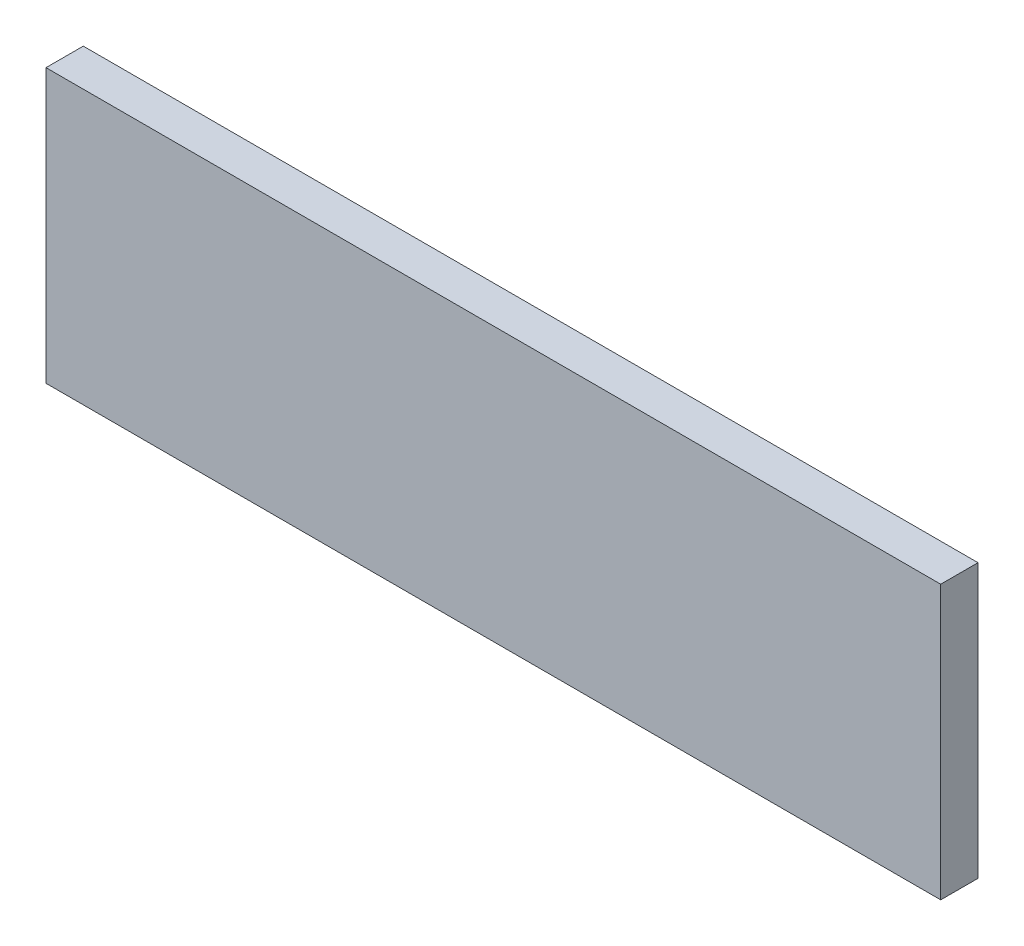
SolidWorks part; units mm, degrees
ref_plane "Front Plane" through (0, 0, 0) normal (0, 0, 1) x (1, 0, 0)
ref_plane "Top Plane" through (0, 0, 0) normal (0, 1, 0) x (1, 0, 0)
ref_plane "Right Plane" through (0, 0, 0) normal (1, 0, 0) x (0, 0, -1)
sketch "Sketch2" plane through (0, 0, 0) normal (0, 0, 1) x (1, 0, 0)
  line L1 (52.3875, 19.05) -> (-61.9125, 19.05)
  line L2 (52.3875, 19.05) -> (52.3875, -15.875)
  line L3 (52.3875, -15.875) -> (-61.9125, -15.875)
  line L4 (-61.9125, 19.05) -> (-61.9125, -15.875)
  dimension "D1" = 114.3
  dimension "D2" = 34.925
extrude "Boss-Extrude1" add sketch "Sketch2" along normal blind 4.7625
